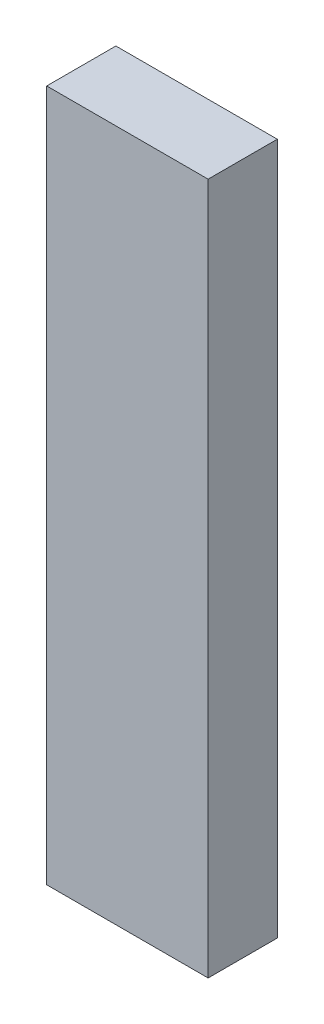
SolidWorks part; units mm, degrees
ref_plane "Front Plane" through (0, 0, 0) normal (0, 0, 1) x (1, 0, 0)
ref_plane "Top Plane" through (0, 0, 0) normal (0, 1, 0) x (1, 0, 0)
ref_plane "Right Plane" through (0, 0, 0) normal (1, 0, 0) x (0, 0, -1)
sketch "Sketch1" plane through (0, 0, 0) normal (0, 0, 1) x (1, 0, 0)
  line L1 (-3.5, 15) -> (3.5, 15)
  line L2 (-3.5, 15) -> (-3.5, -15)
  line L3 (-3.5, -15) -> (3.5, -15)
  line L4 (3.5, 15) -> (3.5, -15)
  line L5 (-3.5, 15) -> (3.5, -15) construction
  line L6 (-3.5, -15) -> (3.5, 15) construction
  point P0 (0, 0)
  dimension "D1" = 30
  dimension "D2" = 7
extrude "Boss-Extrude1" add sketch "Sketch1" along normal blind 3
